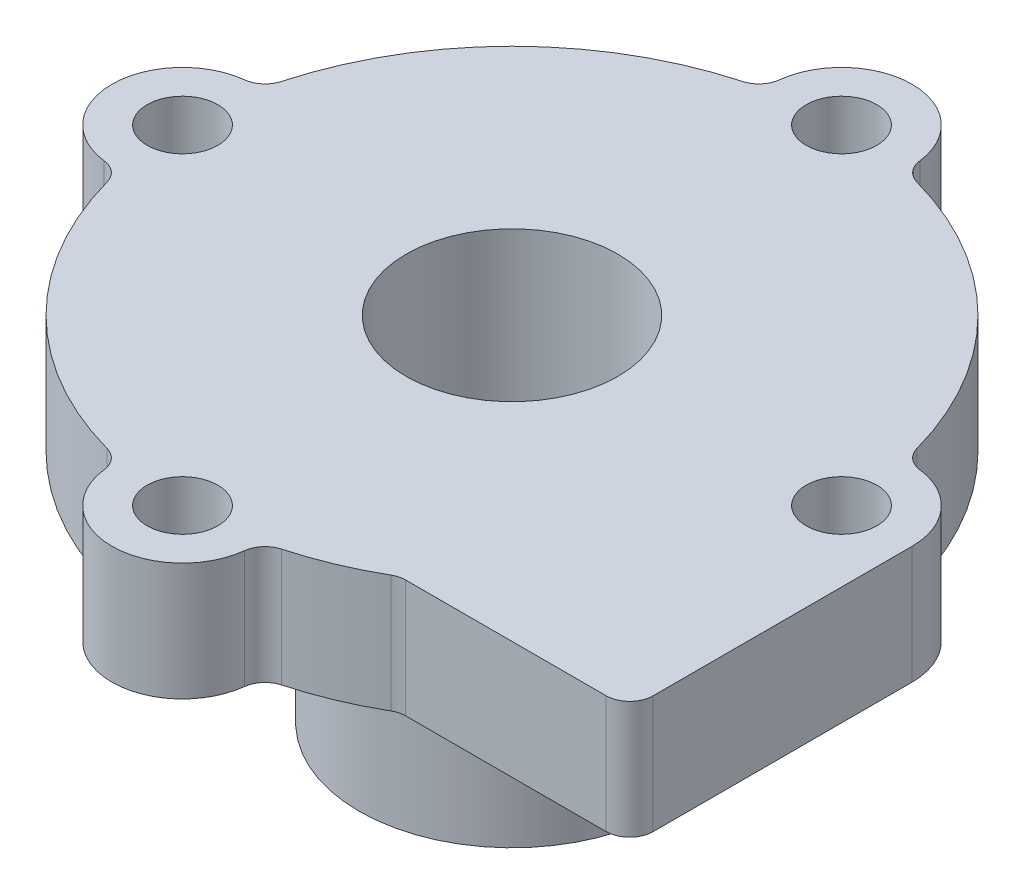
SolidWorks part; units mm, degrees
ref_plane "Front Plane" through (0, 0, 0) normal (0, 0, 1) x (1, 0, 0)
ref_plane "Top Plane" through (0, 0, 0) normal (0, 1, 0) x (1, 0, 0)
ref_plane "Right Plane" through (0, 0, 0) normal (1, 0, 0) x (0, 0, -1)
sketch "Sketch1" plane through (0, 0, 0) normal (0, 1, 0) x (1, 0, 0)
  circle A0 centre (0, 0) radius 14
  circle A1 centre (0, 0) radius 4.5
  dimension "D1" = 28
  dimension "D2" = 9
extrude "Boss-Extrude1" add sketch "Sketch1" along normal blind 5
sketch "Sketch3" plane through (0, 0, 0) normal (0, 1, 0) x (1, 0, 0)
  line L0 (0, -8.25) -> (0, 8.25) construction
  circle A0 centre (0, 14) radius 3
  circle A1 centre (0, 0) radius 14 construction
  dimension "D1" = 6
extrude "Boss-Extrude2" add sketch "Sketch3" along normal blind 5
sketch "Sketch4" plane through (0, 5, 0) normal (0, 1, 0) x (1, 0, 0)
  circle A0 centre (0, 14) radius 1.5
  dimension "D1" = 3
extrude "Cut-Extrude1" cut sketch "Sketch4" against normal blind 5
pattern_circular "CirPattern1" count 4 over 360 about axis through (0, 0, 0) along (0, 1, 0) of "Boss-Extrude2"
sketch "Sketch5" plane through (0, 5, 0) normal (0, 1, 0) x (1, 0, 0)
  line L0 (0, -12) -> (17, -12)
  line L1 (17, -12) -> (17, 0)
  line L2 (17, 0) -> (10.2718, 0)
  line L3 (10.2718, 0) -> (0, -12)
  line L4 (7.4833, -12) -> (16, -12) construction
  arc A0 (13.6786, -2.9827) -> (13.6786, 2.9827) centre (14, 0) ccw construction
extrude "Boss-Extrude3" add sketch "Sketch5" against normal blind 5
pattern_circular "CirPattern2" count 4 over 360 about axis through (0, 0, 0) along (0, 1, 0) of "Cut-Extrude1"
fillet "Fillet1" [suppressed] radius 1
sketch "Sketch6" plane through (0, 0, 0) normal (0, -1, 0) x (1, 0, 0)
  circle A0 centre (0, 0) radius 4.5
  circle A1 centre (0, 0) radius 6.5
  dimension "D1" = 2
  dimension "D2" = 9
extrude "Boss-Extrude4" add sketch "Sketch6" along normal blind 10
fillet "Fillet2" radius 1 10 edges at (13.6786, 2.5, -2.9827) (2.9827, 2.5, -13.6786) (-2.9827, 2.5, -13.6786) (-13.6786, 2.5, -2.9827) (-13.6786, 2.5, 2.9827) (-2.9827, 2.5, 13.6786) (2.9827, 2.5, 13.6786) (7.2111, 2.5, 12) (17, 2.5, 12) (0, 0, 6.5)
